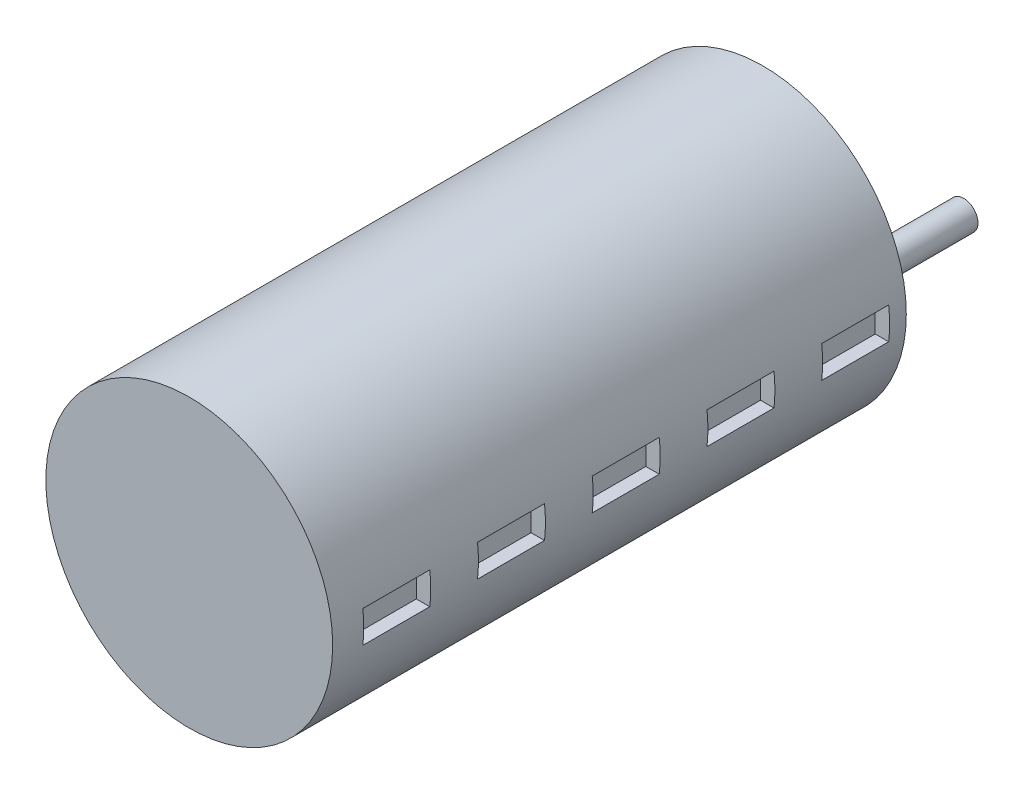
SolidWorks part; units mm, degrees
ref_plane "前视基准面" through (0, 0, 0) normal (0, 0, 1) x (1, 0, 0)
ref_plane "上视基准面" through (0, 0, 0) normal (0, 1, 0) x (1, 0, 0)
ref_plane "右视基准面" through (0, 0, 0) normal (1, 0, 0) x (0, 0, -1)
sketch "草图1" plane through (0, 0, 0) normal (0, 0, 1) x (1, 0, 0)
  circle A0 centre (0, 0) radius 2.5
  dimension "D1" = 5
extrude "凸台-拉伸1" add sketch "草图1" along normal blind 10
sketch "草图2" plane through (0, 0, 0) normal (0, 0, -1) x (-1, 0, 0)
  line L0 (-2.5, 0) -> (2.5, 0) construction
  line L1 (0, 2.5) -> (0, -2.5) construction
  circle A0 centre (0, 0) radius 2.5 construction
  circle A1 centre (-1.5, 0) radius 0.25
  circle A2 centre (1.5, 0) radius 0.25
  dimension "D1" = 0.5
  dimension "D2" = 3
extrude "凸台-拉伸2" add sketch "草图2" along normal blind 2
ref_plane "基准面1" through (2.5, 0, 0) normal (1, 0, 0) x (0, 0, -1)
sketch "草图3" plane through (2.5, 0, 0) normal (1, 0, 0) x (0, 0, -1)
  line L0 (-10, 0) -> (0, 0) construction
  line L1 (-10, 2.5) -> (-10, -2.5) construction
  line L2 (-9.4595, 0.2782) -> (-9.4595, -0.2782)
  line L3 (-9.4595, 0.2782) -> (-8.2917, 0.2782)
  line L4 (-8.2917, 0.2782) -> (-8.2917, -0.2782)
  line L5 (-9.4595, -0.2782) -> (-8.2917, -0.2782)
  line L6 (-7.4595, -0.2782) -> (-6.2917, -0.2782)
  line L7 (-7.4595, 0.2782) -> (-7.4595, -0.2782)
  line L8 (-6.2917, 0.2782) -> (-6.2917, -0.2782)
  line L9 (-7.4595, 0.2782) -> (-6.2917, 0.2782)
  line L10 (-5.4595, -0.2782) -> (-4.2917, -0.2782)
  line L11 (-5.4595, 0.2782) -> (-5.4595, -0.2782)
  line L12 (-4.2917, 0.2782) -> (-4.2917, -0.2782)
  line L13 (-5.4595, 0.2782) -> (-4.2917, 0.2782)
  line L14 (-3.4595, -0.2782) -> (-2.2917, -0.2782)
  line L15 (-3.4595, 0.2782) -> (-3.4595, -0.2782)
  line L16 (-2.2917, 0.2782) -> (-2.2917, -0.2782)
  line L17 (-3.4595, 0.2782) -> (-2.2917, 0.2782)
  line L18 (-1.4595, -0.2782) -> (-0.2917, -0.2782)
  line L19 (-1.4595, 0.2782) -> (-1.4595, -0.2782)
  line L20 (-0.2917, 0.2782) -> (-0.2917, -0.2782)
  line L21 (-1.4595, 0.2782) -> (-0.2917, 0.2782)
  point P10 (-8.2917, 0)
  point P11 (-9.4595, 0)
  dimension "D1" = 5
extrude "切除-拉伸1" cut sketch "草图3" against normal blind 0.25
